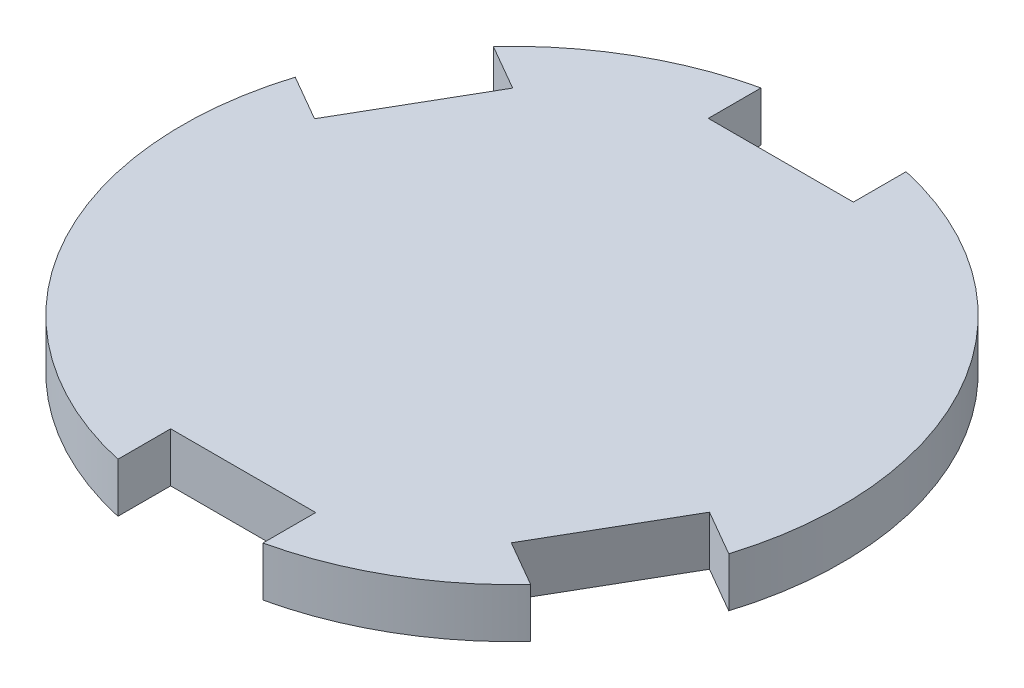
SolidWorks part; units mm, degrees
material "6061-T6 (SS)"
ref_plane "Front Plane" through (0, 0, 0) normal (0, 0, 1) x (1, 0, 0)
ref_plane "Top Plane" through (0, 0, 0) normal (0, 1, 0) x (1, 0, 0)
ref_plane "Right Plane" through (0, 0, 0) normal (1, 0, 0) x (0, 0, -1)
sketch "Sketch1" plane through (0, 0, 0) normal (0, 1, 0) x (1, 0, 0)
  circle A0 centre (0, 0) radius 31.75
  dimension "D1" = 63.5
extrude "Boss-Extrude1" add sketch "Sketch1" along normal blind 4.7625 contours A0
sketch "Sketch2" plane through (0, 4.7625, 0) normal (0, 1, 0) x (1, 0, 0)
  line L0 (0, 0) -> (0, -35.366) construction
  line L1 (0, 0) -> (64.7242, 0) construction
  line L2 (-6.985, -30.9721) -> (-6.985, -25.8921)
  line L3 (-6.985, -25.8921) -> (6.985, -25.8921)
  line L4 (6.985, -25.8921) -> (6.985, -30.9721)
  line L5 (-6.985, 30.9721) -> (-6.985, 25.8921)
  line L6 (6.985, 25.8921) -> (6.985, 30.9721)
  line L7 (-6.985, 25.8921) -> (6.985, 25.8921)
  circle A0 centre (0, 0) radius 31.75 construction
  arc A1 (-6.985, -30.9721) -> (6.985, -30.9721) centre (0, 0) ccw
  arc A2 (-6.985, 30.9721) -> (6.985, 30.9721) centre (0, 0) cw
  point P13 (0, -25.8921)
  dimension "D1" = 5.08
  dimension "D2" = 13.97
sketch "Sketch3" plane through (0, 4.7625, 0) normal (0, 1, 0) x (1, 0, 0)
  line L0 (0, 0) -> (36.6359, -21.1517) construction
  line L1 (0, 200000) -> (0, -200035.366) construction
  line L2 (18.9307, -18.9952) -> (25.9157, -6.8969)
  line L3 (18.9307, -18.9952) -> (23.3301, -21.5352)
  line L4 (25.9157, -6.8969) -> (30.3151, -9.4369)
  line L5 (0, 0) -> (24.0523, 41.6598) construction
  line L6 (-25.9157, 6.8969) -> (-30.3151, 9.4369)
  line L7 (-18.9307, 18.9952) -> (-23.3301, 21.5352)
  line L8 (-25.9157, 6.8969) -> (-18.9307, 18.9952)
  circle A0 centre (0, 0) radius 31.75 construction
  arc A1 (23.3301, -21.5352) -> (30.3151, -9.4369) centre (0, 0) ccw
  arc A2 (-30.3151, 9.4369) -> (-23.3301, 21.5352) centre (0, 0) cw
  point P8 (22.4232, -12.9461)
  dimension "D1" = 60
  dimension "D2" = 5.08
  dimension "D3" = 13.97
extrude "Cut-Extrude1" cut sketch "Sketch2" against normal up to next
extrude "Cut-Extrude2" cut sketch "Sketch3" against normal up to next contours A1 L4 L2 L3 | A2 L7 L8 L6
